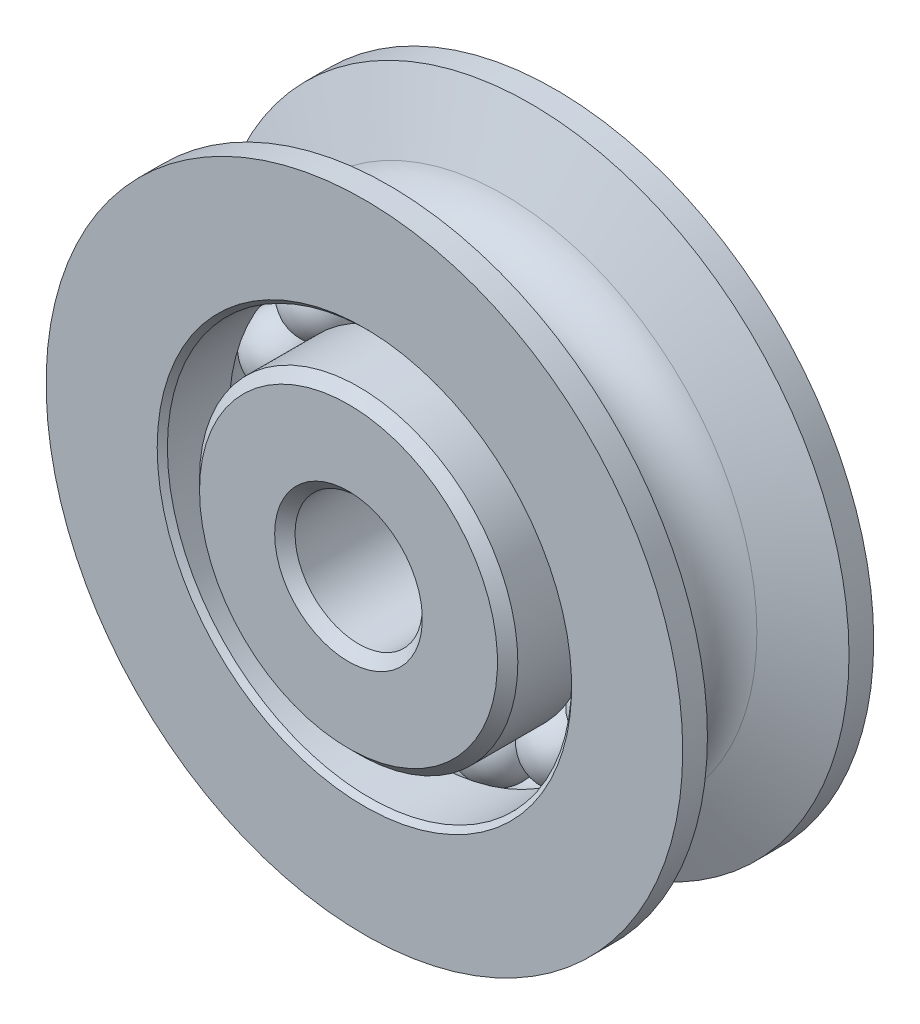
SolidWorks part; units mm, degrees
ref_plane "Front" through (0, 0, 0) normal (0, 0, 1) x (1, 0, 0)
ref_plane "Top" through (0, 0, 0) normal (0, 1, 0) x (1, 0, 0)
ref_plane "Right" through (0, 0, 0) normal (1, 0, 0) x (0, 0, -1)
sketch "Sketch1" plane through (0, 0, 0) normal (1, 0, 0) x (0, 0, -1)
  line L0 (3.5306, 15.875) -> (4.7625, 15.875)
  line L1 (-3.5306, 15.875) -> (-4.7625, 15.875)
  line L2 (-3.5306, 15.875) -> (-2.2078, 12.6016)
  line L3 (1.4287, 10.0806) -> (4.7625, 10.0806)
  line L4 (5.5562, 3.175) -> (-5.5562, 3.175)
  line L5 (-1.4287, 7.9375) -> (-5.5563, 7.9375)
  line L6 (3.5306, 15.875) -> (2.2078, 12.6016)
  line L8 (-5.5562, 0) -> (5.5562, 0) construction
  line L10 (4.7625, 15.875) -> (4.7625, 10.0806)
  line L13 (-5.5563, 7.9375) -> (-5.5562, 3.175)
  line L14 (0, 11.1125) -> (0, -11.1125) construction
  line L16 (5.5563, 7.9375) -> (5.5562, 3.175)
  line L17 (-4.7625, 15.875) -> (-4.7625, -15.875) construction
  line L18 (-4.7625, 10.0806) -> (-1.4287, 10.0806)
  line L20 (5.5563, 7.9375) -> (1.4287, 7.9375)
  line L21 (-4.7625, 10.0806) -> (-4.7625, 15.875)
  arc A0 (-2.2078, 12.6016) -> (2.2078, 12.6016) centre (0, 13.4938) ccw
  circle A1 centre (0, 13.4938) radius 2.3813 construction
  circle A2 centre (0, 0) radius 3.175 construction
  circle A3 centre (0, 0) radius 7.9375 construction
  arc A4 (-1.4287, 7.9375) -> (1.4287, 7.9375) centre (0, 9.0091) ccw
  circle A5 centre (0, -13.4937) radius 2.3813 construction
  arc A6 (1.4287, 10.0806) -> (-1.4287, 10.0806) centre (0, 9.0091) ccw
  point P28 (-4.7625, 0)
  dimension "Rope Dia" = 4.7625
  dimension "D1" = 15.875
  dimension "Shaft Dia" = 6.35
  dimension "D3" = 2.1431
  dimension "D2" = 3.5719
  dimension "Wd" = 11.1125
  dimension "D8" = 1.2319
  dimension "Groove Dia" = 22.225
  dimension "OD" = 31.75
  dimension "w Wd" = 9.525
revolve "Revolve1" add sketch "Sketch1" angle 360 about L8
sketch "Sketch2" plane through (0, 0, 0) normal (1, 0, 0) x (0, 0, -1)
  line L0 (0, 11.1125) -> (0, -11.1125) construction
  line L1 (0, 10.795) -> (0, 7.2231)
  arc A0 (1.4287, 10.0806) -> (-1.4287, 10.0806) centre (0, 9.0091) ccw construction
  arc A1 (0, 7.2231) -> (0, 10.795) centre (0, 9.0091) ccw
revolve "Revolve2" add sketch "Sketch2" angle 360 about L1
pattern_circular "CirPattern1" count 15 over 360 about axis through (0, 0, 0) along (0, 0, 1) of bodies 117
chamfer "Chamfer1" distance 0.508 angle 45 4 edges at (3.175, 0, -5.5562) (7.9375, 0, -5.5563) (7.9375, 0, 5.5563) (3.175, 0, 5.5562)
chamfer "Chamfer2" distance 0.254 angle 45 2 edges at (10.0806, 0, -4.7625) (10.0806, 0, 4.7625)
equation "\"D1@Sketch1\" = \"Shaft Dia@Sketch1\" * 2.5"
equation "\"D2@Sketch1\" = \"Rope Dia@Sketch1\" * .75"
equation "\"D3@Sketch1\" = \"D2@Sketch1\" * .6"
